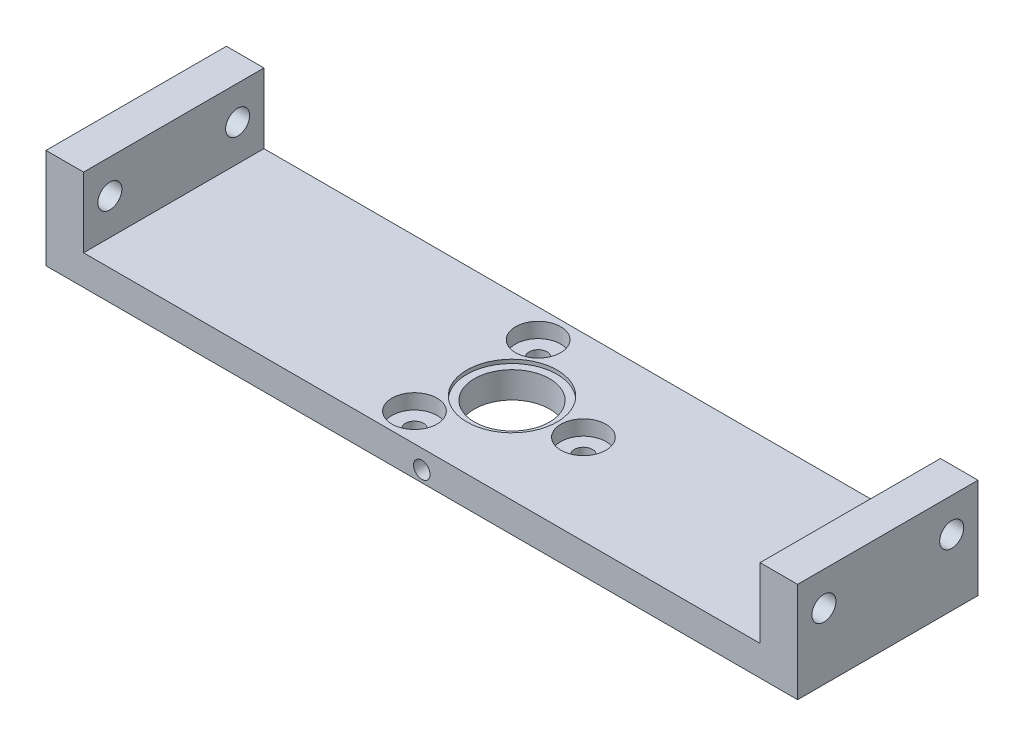
SolidWorks part; units mm, degrees
ref_plane "前视基准面" through (0, 0, 0) normal (0, 0, 1) x (1, 0, 0)
ref_plane "上视基准面" through (0, 0, 0) normal (0, 1, 0) x (1, 0, 0)
ref_plane "右视基准面" through (0, 0, 0) normal (1, 0, 0) x (0, 0, -1)
other "Configuration Table"
sketch "草图1" plane through (0, 0, 0) normal (0, 1, 0) x (1, 0, 0)
  line L1 (-50, 12) -> (50, 12)
  line L2 (-50, 12) -> (-50, -12)
  line L3 (-50, -12) -> (50, -12)
  line L4 (50, 12) -> (50, -12)
  line L5 (-50, 12) -> (50, -12) construction
  line L6 (-50, -12) -> (50, 12) construction
  point P0 (0, 0)
  dimension "D1" = 100
  dimension "D2" = 24
extrude "凸台-拉伸1" add sketch "草图1" along normal blind 13.3
sketch "草图2" plane through (0, 13.3, 0) normal (0, 1, 0) x (1, 0, 0)
  line L0 (0, 34.9924) -> (0, -36.2384) construction
  line L1 (-45, 12) -> (-45, -12)
  line L2 (45, 12) -> (45, -12)
  line L3 (-50, -12) -> (50, -12) construction
  line L4 (50, 12) -> (-50, 12) construction
  line L5 (-45, -12) -> (45, -12)
  line L6 (45, 12) -> (-45, 12)
  line L8 (-45, 34.9924) -> (-45, -36.2384) construction
  line L9 (45, 34.9924) -> (45, -36.2384) construction
  dimension "D1" = 45
  dimension "D2" = 45
extrude "切除-拉伸1" cut sketch "草图2" against normal blind 9.3
sketch "草图3" plane through (50, 0, 0) normal (1, 0, 0) x (0, 0, -1)
  line L0 (0, -4.0303) -> (0, 26.6544) construction
  line L1 (8.5, -4.0303) -> (8.5, 26.6544) construction
  line L2 (-8.5, -4.0303) -> (-8.5, 26.6544) construction
  line L7 (-12, 8.8) -> (12, 8.8)
  line L8 (-12, 8.8) -> (12, 8.8) construction
  point P15 (-8.5, 8.8)
  point P17 (8.5, 8.8)
  dimension "D1" = 8.5
  dimension "D2" = 8.5
  dimension "D4" = 8.8
hole_wizard "Ø3.2 (3.2) 直径孔1" positions "草图3" profile "草图4" hole size "Ø3.2" standard "GB" end condition through all
sketch "草图4" plane through (50, 8.8, -8.5) normal (0, 1, 0) x (0, 0, -1)
  line L0 (0, 0) -> (0, 100)
  line L1 (0, 100) -> (1.6, 100)
  line L2 (1.6, 100) -> (1.6, 0)
  line L5 (1.6, 0) -> (0, 0)
  line L11 (0, -6.35) -> (0, 107.95) construction
  dimension "通孔孔直径" = 3.2
  dimension "通孔孔深度" = 100
sketch "草图5" plane through (0, 4, 0) normal (0, 1, 0) x (1, 0, 0)
  circle A0 centre (0, 0) radius 5
  dimension "D1" = 10
extrude "切除-拉伸2" cut sketch "草图5" against normal through all
sketch "草图6" plane through (0, 4, 0) normal (0, 1, 0) x (1, 0, 0)
  circle A0 centre (0, 0) radius 6
  dimension "D1" = 12
extrude "切除-拉伸3" cut sketch "草图6" against normal blind 0.5
sketch "草图7" plane through (0, 4, 0) normal (0, 1, 0) x (1, 0, 0)
  line L0 (-53.1635, 0) -> (64.5854, 0) construction
  line L1 (0, 28.6585) -> (0, -25.0242) construction
  line L2 (9.5, 28.6585) -> (9.5, -25.0242) construction
  point P7 (9.5, 0)
  dimension "D1" = 9.5
hole_wizard "M2 六角头螺栓的柱形沉头孔1" positions "草图7" profile "草图8" counterbore size "M2" standard "GB" end condition up to next
sketch "草图8" plane through (9.5, 4, 0) normal (1, 0, 0) x (0, 0, 1)
  line L0 (0, 0) -> (0, 4)
  line L1 (0, 4) -> (1.2, 4)
  line L3 (1.2, 4) -> (1.2, 2)
  line L4 (1.2, 2) -> (3, 2)
  line L5 (3, 2) -> (3, 0)
  line L7 (3, 0) -> (0, 0)
  line L11 (0, -6.35) -> (0, 107.95) construction
  dimension "通孔孔直径" = 2.4
  dimension "通孔孔深度" = 4
  dimension "柱形沉头孔直径" = 6
  dimension "柱形沉头孔深度" = 2
pattern_circular "阵列(圆周)1" count 3 every 120 about axis through (0, 0, 0) along (0, 1, 0) of "M2 六角头螺栓的柱形沉头孔1"
sketch "草图9" plane through (0, 0, 12) normal (0, 0, 1) x (1, 0, 0)
  line L0 (0, 31.4666) -> (0, -16.0899) construction
  line L3 (-45, 1.5) -> (45, 1.5)
  line L4 (-45, 1.5) -> (45, 1.5) construction
  circle A0 centre (0, 1.5) radius 1.1
  dimension "D2" = 2.2
  dimension "D1" = 2.5
extrude "切除-拉伸4" cut sketch "草图9" against normal blind 10
